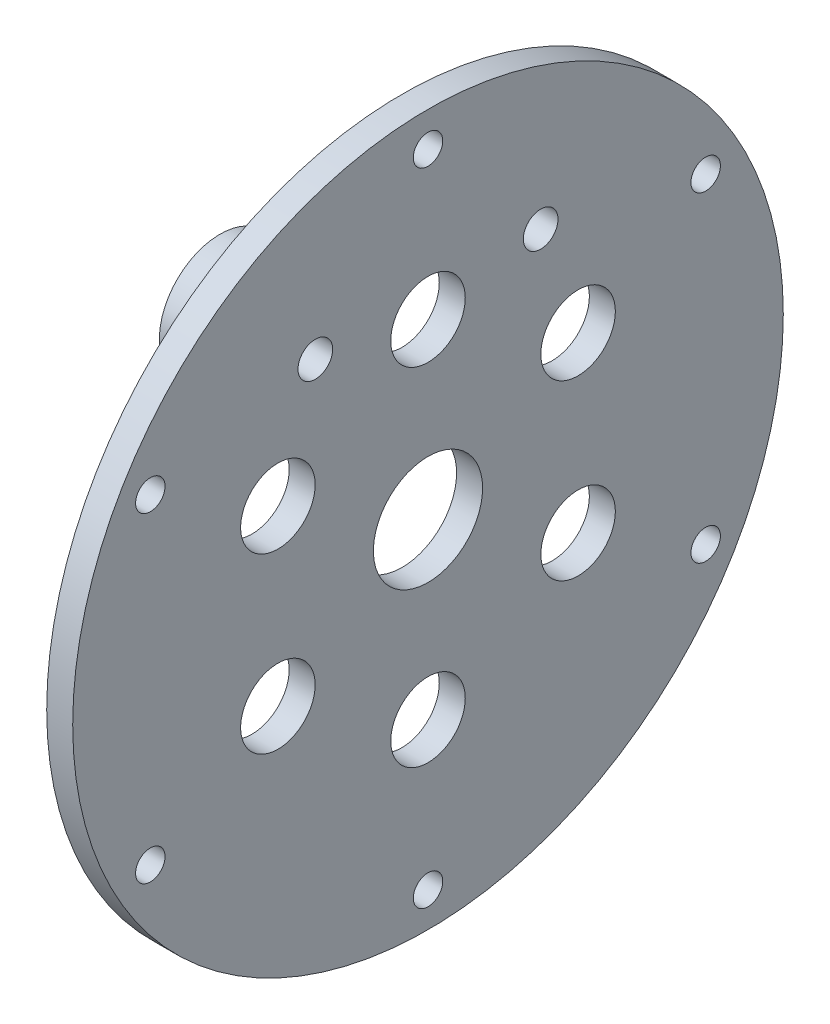
SolidWorks part; units mm, degrees
ref_plane "Front Plane" through (0, 0, 0) normal (0, 0, 1) x (1, 0, 0)
ref_plane "Top Plane" through (0, 0, 0) normal (0, 1, 0) x (1, 0, 0)
ref_plane "Right Plane" through (0, 0, 0) normal (1, 0, 0) x (0, 0, -1)
sketch "Axial blank profile" plane through (0, 0, 0) normal (0, 0, 1) x (1, 0, 0)
  line L0 (-60, 0) -> (30, 0) construction
  line L1 (-3, 0) -> (0, 0)
  line L2 (0, 0) -> (0, 41)
  line L3 (0, 41) -> (-3, 41)
  line L4 (-3, 41) -> (-3, 0)
revolve "Native revolved blank" add sketch "Axial blank profile" angle 360 about L0
sketch "Relocated integral port bosses between magnets sketch" plane through (0, 0, 0) normal (1, 0, 0) x (0, 0, -1)
  circle A0 centre (-13, 22.5167) radius 7
  circle A1 centre (13, 22.5167) radius 7
extrude "Relocated integral port bosses between magnets" add sketch "Relocated integral port bosses between magnets sketch" along normal blind 8 from offset 11
sketch "Seven dry magnet passages through cover sketch" plane through (0, 0, 0) normal (1, 0, 0) x (0, 0, -1)
  circle A0 centre (0, 0) radius 6.3
  circle A1 centre (0, 20) radius 4.3
  circle A2 centre (-17.3205, 10) radius 4.3
  circle A3 centre (-17.3205, -10) radius 4.3
  circle A4 centre (0, -20) radius 4.3
  circle A5 centre (17.3205, -10) radius 4.3
  circle A6 centre (17.3205, 10) radius 4.3
extrude "Seven dry magnet passages through cover" cut sketch "Seven dry magnet passages through cover sketch" along normal blind 3 from offset 3
sketch "Six cover clearance holes PCD74 sketch" plane through (0, 0, 0) normal (1, 0, 0) x (0, 0, -1)
  circle A0 centre (0, 37) radius 1.7
  circle A1 centre (-32.0429, 18.5) radius 1.7
  circle A2 centre (-32.0429, -18.5) radius 1.7
  circle A3 centre (0, -37) radius 1.7
  circle A4 centre (32.0429, -18.5) radius 1.7
  circle A5 centre (32.0429, 18.5) radius 1.7
extrude "Six cover clearance holes PCD74" cut sketch "Six cover clearance holes PCD74 sketch" along normal blind 3 from offset 3
sketch "G1-8 tapping pilot envelopes depth7 sketch" plane through (0, 0, 0) normal (1, 0, 0) x (0, 0, -1)
  circle A0 centre (-13, 22.5167) radius 4.4
  circle A1 centre (13, 22.5167) radius 4.4
extrude "G1-8 tapping pilot envelopes depth7" cut sketch "G1-8 tapping pilot envelopes depth7 sketch" along normal blind 7 from offset 11
sketch "Water ports diameter4 into coolant plenum sketch" plane through (0, 0, 0) normal (1, 0, 0) x (0, 0, -1)
  circle A0 centre (-13, 22.5167) radius 2
  circle A1 centre (13, 22.5167) radius 2
extrude "Water ports diameter4 into coolant plenum" cut sketch "Water ports diameter4 into coolant plenum sketch" along normal blind 11 from offset 11
